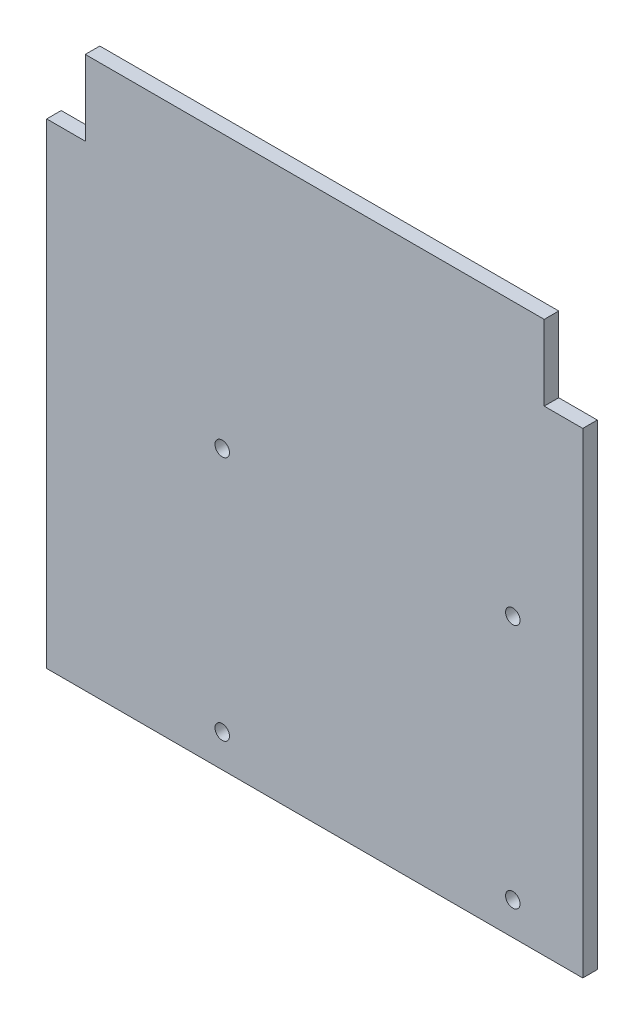
SolidWorks part; units mm, degrees
ref_plane "Front Plane" through (0, 0, 0) normal (0, 0, 1) x (1, 0, 0)
ref_plane "Top Plane" through (0, 0, 0) normal (0, 1, 0) x (1, 0, 0)
ref_plane "Right Plane" through (0, 0, 0) normal (1, 0, 0) x (0, 0, -1)
sketch "Sketch1" plane through (0, 0, 0) normal (0, 0, 1) x (1, 0, 0)
  line L4 (0, -47.5) -> (0, 75.1224) construction
  line L5 (-53.5, -47.5) -> (53.5, -47.5)
  line L6 (-53.5, -47.5) -> (-53.5, 47.5)
  line L7 (-53.5, 47.5) -> (-45.802, 47.5)
  line L8 (53.5, -47.5) -> (53.5, 47.5)
  line L9 (-53.5, -47.5) -> (53.5, 47.5) construction
  line L10 (-53.5, 47.5) -> (53.5, -47.5) construction
  line L11 (0, 0) -> (92.3064, 0) construction
  line L12 (48, 57.5289) -> (48, -67.5733) construction
  line L13 (-48, 56.5105) -> (-48, -72.884) construction
  line L14 (-42, -16.4523) -> (43, -16.4523) construction
  line L15 (39.5367, -54.9766) -> (39.5367, 8.0477) construction
  line L16 (43.0367, 11.5477) -> (-42.0367, 11.5477) construction
  line L17 (43.0367, 11.5477) -> (43.0367, -44.4523) construction
  line L18 (43.0367, -44.4523) -> (-42.0367, -44.4523) construction
  line L19 (-42.0367, 11.5477) -> (-42.0367, -44.4523) construction
  line L20 (43.0367, 11.5477) -> (-42.0367, -44.4523) construction
  line L21 (43.0367, -44.4523) -> (-42.0367, 11.5477) construction
  line L22 (39.5367, -40.9523) -> (-18.4633, -40.9523) construction
  line L23 (39.5367, 8.0477) -> (-18.4633, 8.0477) construction
  line L24 (45.802, 47.5) -> (53.5, 47.5)
  line L26 (45.802, 47.5) -> (45.802, 62.5)
  line L27 (45.802, 62.5) -> (-45.802, 62.5)
  line L28 (-45.802, 47.5) -> (-45.802, 62.5)
  line L29 (45.802, 16.5583) -> (-45.802, 62.5) construction
  line L30 (45.802, 62.5) -> (-45.802, 16.5583) construction
  circle A0 centre (39.5367, -40.9523) radius 1.45
  circle A1 centre (39.5367, 8.0477) radius 1.45
  circle A2 centre (-18.4633, -40.9523) radius 1.45
  circle A3 centre (-18.4633, 8.0477) radius 1.45
  point P0 (0, 0)
  point P12 (0.5, -16.4523)
  point P15 (0.5, -16.4523)
  point P31 (0, -47.5)
  point P32 (0, 39.5291)
  dimension "D3" = 5.5
  dimension "D10" = 2.9
  dimension "D11" = 2.9
  dimension "D13" = 2.9
  dimension "D14" = 2.9
  dimension "D1" = 107
  dimension "D2" = 95
  dimension "D4" = 5.5
  dimension "D5" = 85
  dimension "D6" = 56
  dimension "D7" = 3.5
  dimension "D8" = 3.5
  dimension "D9" = 49
  dimension "D12" = 58
  dimension "D15" = 58
  dimension "D16" = 0.5
  dimension "D17" = 15
extrude "Boss-Extrude2" add sketch "Sketch1" along normal blind 2.9
